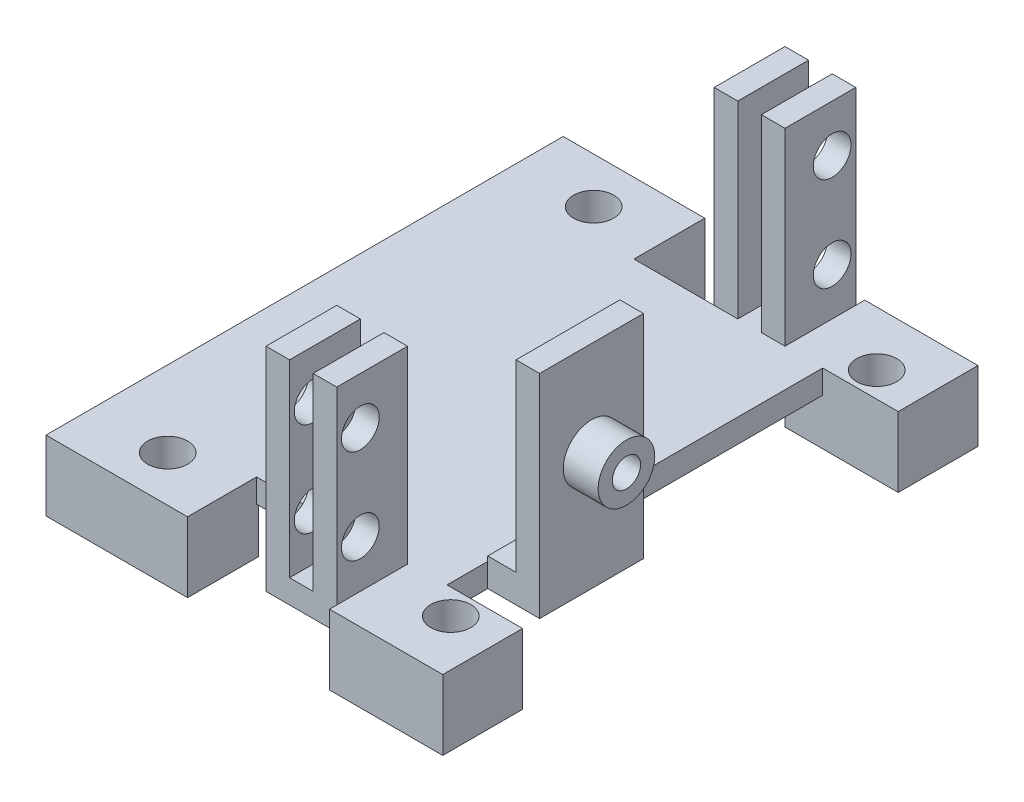
SolidWorks part; units mm, degrees
ref_plane "前视基准面" through (0, 0, 0) normal (0, 0, 1) x (1, 0, 0)
ref_plane "上视基准面" through (0, 0, 0) normal (0, 1, 0) x (1, 0, 0)
ref_plane "右视基准面" through (0, 0, 0) normal (1, 0, 0) x (0, 0, -1)
other "Configuration Table"
sketch "草图1" plane through (0, 0, 0) normal (0, 1, 0) x (1, 0, 0)
  line L1 (-105.8589, 60.8313) -> (105.8589, 60.8313)
  line L2 (-105.8589, 60.8313) -> (-105.8589, -60.8313)
  line L3 (-105.8589, -60.8313) -> (105.8589, -60.8313)
  line L4 (105.8589, 60.8313) -> (105.8589, -60.8313)
  line L5 (-105.8589, 60.8313) -> (105.8589, -60.8313) construction
  line L6 (-105.8589, -60.8313) -> (105.8589, 60.8313) construction
  point P0 (0, 0)
extrude "凸台-拉伸1" add sketch "草图1" along normal blind 10
sketch "草图2" plane through (0, 10, 0) normal (0, 1, 0) x (1, 0, 0)
  line L1 (-48.8589, 39.8117) -> (-43.8589, 39.8117)
  line L2 (-48.8589, 39.8117) -> (-48.8589, 54.8117)
  line L3 (-48.8589, 54.8117) -> (-43.8589, 54.8117)
  line L4 (-43.8589, 39.8117) -> (-43.8589, 54.8117)
  line L5 (-53.8589, 39.8117) -> (-58.8589, 39.8117)
  line L6 (-53.8589, 39.8117) -> (-53.8589, 54.8117)
  line L7 (-53.8589, 54.8117) -> (-58.8589, 54.8117)
  line L8 (-58.8589, 39.8117) -> (-58.8589, 54.8117)
  line L9 (-48.8589, -40.1883) -> (-43.8589, -40.1883)
  line L10 (-48.8589, -40.1883) -> (-48.8589, -55.1883)
  line L11 (-48.8589, -55.1883) -> (-43.8589, -55.1883)
  line L12 (-43.8589, -40.1883) -> (-43.8589, -55.1883)
  line L13 (-53.8589, -40.1883) -> (-58.8589, -40.1883)
  line L14 (-53.8589, -40.1883) -> (-53.8589, -55.1883)
  line L15 (-53.8589, -55.1883) -> (-58.8589, -55.1883)
  line L16 (-58.8589, -40.1883) -> (-58.8589, -55.1883)
  dimension "D1" = 5
  dimension "D2" = 5
  dimension "D3" = 15
  dimension "D4" = 15
  dimension "D5" = 5
  dimension "D6" = 5
  dimension "D7" = 15
  dimension "D8" = 15
extrude "凸台-拉伸2" add sketch "草图2" along normal up to surface (40 mm away)
sketch "草图3" plane through (0, 10, 0) normal (0, 1, 0) x (1, 0, 0)
  line L0 (-105.8589, 39.8117) -> (-58.8589, 39.8117)
  line L1 (-105.8589, 60.8313) -> (-105.8589, -60.8313) construction
  line L2 (-58.8589, 39.8117) -> (-58.8589, 54.8117)
  line L3 (-58.8589, 54.8117) -> (-43.8589, 54.8117)
  line L4 (-43.8589, 54.8117) -> (-43.8589, 39.8117)
  line L5 (-43.8589, 39.8117) -> (-35.8589, 39.8117)
  line L6 (-35.8589, 39.8117) -> (-35.8589, -40.1883)
  line L7 (-35.8589, -40.1883) -> (-43.8589, -40.1883)
  line L8 (-43.8589, -40.1883) -> (-43.8589, -55.1883)
  line L9 (-43.8589, -55.1883) -> (-48.8589, -55.1883)
  line L10 (-48.8589, -55.1883) -> (-48.8589, -40.1883)
  line L11 (-48.8589, -40.1883) -> (-53.8589, -40.1883)
  line L12 (-53.8589, -40.1883) -> (-53.8589, -55.1883)
  line L13 (-53.8589, -55.1883) -> (-58.8589, -55.1883)
  line L14 (-58.8589, -55.1883) -> (-58.8589, -40.1883)
  line L15 (-58.8589, -40.1883) -> (-106.7148, -40.1883)
  line L16 (-106.7148, -40.1883) -> (-105.8589, 39.8117)
extrude "切除-拉伸1" cut sketch "草图3" against normal through all both and the other way through all flip side to cut
sketch "草图4" plane through (0, 0, 0) normal (0, -1, 0) x (1, 0, 0)
  line L0 (-43.8589, 40.1883) -> (-35.8589, 40.1883) construction
  line L1 (-58.8589, 55.1883) -> (-43.8589, 55.1883)
  line L2 (-58.8589, 55.1883) -> (-58.8589, 40.1883)
  line L3 (-58.8589, 40.1883) -> (-43.8589, 40.1883)
  line L4 (-43.8589, 55.1883) -> (-43.8589, 40.1883)
  line L5 (-43.8589, 55.1883) -> (-43.8589, 40.1883) construction
extrude "凸台-拉伸3" add sketch "草图4" against normal blind 10
sketch "草图5" plane through (0, 0, 0) normal (0, -1, 0) x (1, 0, 0)
  line L1 (-225.4861, 144.4064) -> (25.5621, 144.4064)
  line L2 (-225.4861, 144.4064) -> (-225.4861, -64.4322)
  line L3 (-225.4861, -64.4322) -> (25.5621, -64.4322)
  line L4 (25.5621, 144.4064) -> (25.5621, -64.4322)
extrude "切除-拉伸2" cut sketch "草图5" against normal blind 5 and the other way through all
sketch "草图7" plane through (-43.8589, 0, 0) normal (1, 0, 0) x (0, 0, -1)
  circle A0 centre (-50.1883, 40) radius 4
  circle A1 centre (-50.1883, 20) radius 4
  circle A2 centre (49.8117, 40) radius 4
  circle A3 centre (49.8117, 20) radius 4
extrude "切除-拉伸3" cut sketch "草图7" against normal through all both and the other way through all
sketch "草图8" plane through (0, 5, 0) normal (0, -1, 0) x (1, 0, 0)
  line L0 (-126.1066, 20.1883) -> (-2.0025, 20.1883)
  line L1 (-17.4589, -19.8117) -> (-130.3567, -19.8117)
  line L2 (-17.4589, -25.8117) -> (-17.4589, -13.8117) construction
  line L4 (-43.8589, 40.1883) -> (-35.8589, 40.1883) construction
  line L6 (-29.8589, -19.8117) -> (-29.8589, 25.3599) construction
  line L7 (-35.8589, 40.1883) -> (-35.8589, -39.8117) construction
  line L9 (-35.8589, 31.1883) -> (-29.8589, 31.1883)
  line L10 (-35.8589, 31.1883) -> (-35.8589, 9.1883)
  line L11 (-35.8589, 9.1883) -> (-29.8589, 9.1883)
  line L12 (-29.8589, 31.1883) -> (-29.8589, 9.1883)
  dimension "D1" = 20
  dimension "D2" = 11
  dimension "D3" = 11
  dimension "D4" = 0
extrude "凸台-拉伸6" add sketch "草图8" against normal up to surface (6 mm away) contours L10 L9 L12 L11
sketch "草图9" plane through (0, 5, 0) normal (0, -1, 0) x (1, 0, 0)
  line L0 (-34.8589, 39.1883) -> (-34.8589, 31.1883)
  line L1 (-34.8589, 31.1883) -> (-29.2078, 25.5372)
  line L2 (-29.2078, 25.5372) -> (-29.2078, 39.1883)
  line L3 (-29.2078, 39.1883) -> (-34.8589, 39.1883)
extrude "切除-拉伸4" cut sketch "草图9" against normal through all both and the other way through all
sketch "草图10" plane through (-29.8589, 0, 0) normal (1, 0, 0) x (0, 0, -1)
  line L0 (19.8117, 30) -> (54.8117, 30)
  line L1 (-9.1883, 5) -> (-31.1883, 5)
  line L2 (-9.1883, 5) -> (-9.1883, 50)
  line L3 (-9.1883, 50) -> (-31.1883, 50)
  line L4 (-31.1883, 5) -> (-31.1883, 50)
  line L5 (54.8117, 50) -> (54.8117, 5) construction
  line L6 (-55.1883, 30) -> (-20.1883, 30) construction
  line L7 (-55.1883, 50) -> (-55.1883, 5) construction
  line L8 (-20.1883, 57.2172) -> (-20.1883, -20.7993) construction
  line L9 (-9.1883, 5) -> (39.8117, 5) construction
  line M8 (-9.1883, 11) -> (-26.1883, 11)
  line M9 (-26.1883, 11) -> (-26.1883, 5)
  line M10 (-26.1883, 5) -> (-9.1883, 5)
  line M11 (-9.1883, 5) -> (-9.1883, 11)
  dimension "D2" = 11
  dimension "D1" = 35
  dimension "D3" = 45
extrude "凸台-拉伸7" add sketch "草图10" along normal blind 5 contours L4 L1 L2 L3 M9 M8 | M11 M8 M9 M10
sketch "草图11" plane through (-24.8589, 0, 0) normal (1, 0, 0) x (0, 0, -1)
  line L0 (-20.1883, 50) -> (-20.1883, 5) construction
  line L1 (-9.1883, 50) -> (-31.1883, 50) construction
  line L2 (-9.1883, 5) -> (-31.1883, 5) construction
  line L3 (-9.1883, 27.5) -> (-31.1883, 27.5) construction
  line L4 (-9.1883, 5) -> (-9.1883, 50) construction
  line L5 (-31.1883, 5) -> (-31.1883, 50) construction
  circle A0 centre (-20.1883, 27.5) radius 11
  dimension "D1" = 22
extrude "凸台-拉伸8" add sketch "草图11" against normal up to surface (0.6 mm away)
sketch "草图12" plane through (-24.8589, 0, 0) normal (1, 0, 0) x (0, 0, -1)
  line L0 (-20.1883, 50) -> (-20.1883, 5) construction
  line L1 (-9.1883, 50) -> (-31.1883, 50) construction
  line L2 (-9.1883, 5) -> (-31.1883, 5) construction
  line L3 (-9.1883, 27.5) -> (-31.1883, 27.5) construction
  line L4 (-9.1883, 5) -> (-9.1883, 50) construction
  line L5 (-31.1883, 5) -> (-31.1883, 50) construction
  circle A0 centre (-20.1883, 27.5) radius 6
  dimension "D1" = 12
extrude "凸台-拉伸9" add sketch "草图12" along normal up to surface (7.4 mm away) contours A0
sketch "草图13" plane through (-17.4589, 0, 0) normal (1, 0, 0) x (0, 0, -1)
  circle A0 centre (-20.1883, 27.5) radius 3
  dimension "D1" = 6
extrude "切除-拉伸10" cut sketch "草图13" against normal blind 3 and the other way through all
sketch "草图14" plane through (0, 5, 0) normal (0, -1, 0) x (-1, 0, 0)
  line L0 (34.8589, -31.1883) -> (29.8589, -31.1883)
  line L1 (29.8589, -31.1883) -> (29.8589, -26.1883)
  line L2 (29.8589, -26.1883) -> (34.8589, -31.1883)
extrude "凸台-拉伸10" add sketch "草图14" against normal up to surface (45 mm away) up to face at (-27.3589, 50, 20.1883)
sketch "草图15" plane through (-24.8589, 0, 0) normal (1, 0, 0) x (0, 0, -1)
  circle A0 centre (-20.1883, 27.5) radius 9.3191
extrude "切除-拉伸11" cut sketch "草图15" along normal blind 38
sketch "草图16" plane through (-24.8589, 0, 0) normal (1, 0, 0) x (0, 0, -1)
  line L0 (19.8117, 30) -> (-62.797, 30) construction
  line L1 (-20.1883, 50) -> (-20.1883, 5) construction
  line L2 (-9.1883, 50) -> (-31.1883, 50) construction
  line L3 (-9.1883, 5) -> (-31.1883, 5) construction
  circle A0 centre (-20.1883, 30) radius 6
  dimension "D1" = 12
extrude "凸台-拉伸11" add sketch "草图16" along normal up to surface (7.4 mm away)
sketch "草图17" plane through (-17.4589, 0, 0) normal (1, 0, 0) x (0, 0, -1)
  circle A0 centre (-20.1883, 30) radius 3
  dimension "D1" = 6
extrude "切除-拉伸12" cut sketch "草图17" against normal blind 5
ref_plane "基准面1" through (0, 0, 0.1883) normal (0, 0, -1) x (-1, 0, 0)
sketch "草图18" plane through (0, 10, 0) normal (0, 1, 0) x (1, 0, 0)
  line L0 (-105.8589, 39.8117) -> (-105.8589, -40.1883) construction
  line L5 (-105.8589, 39.8117) -> (-75.8589, 39.8117)
  line L6 (-105.8589, 39.8117) -> (-105.8589, 54.8117)
  line L7 (-105.8589, 54.8117) -> (-75.8589, 54.8117)
  line L8 (-75.8589, 39.8117) -> (-75.8589, 54.8117)
  line L9 (-58.8589, 39.8117) -> (-105.8589, 39.8117) construction
  dimension "D1" = 30
  dimension "D2" = 15
extrude "凸台-拉伸12" add sketch "草图18" against normal up to surface (14.8505 mm away)
sketch "草图19" plane through (0, 10, 0) normal (0, 1, 0) x (1, 0, 0)
  circle A0 centre (-89.7427, 45.1412) radius 4.25
sketch "草图20" plane through (0, 10, 0) normal (0, 1, 0) x (1, 0, 0)
  line L1 (-105.8589, -40.1883) -> (-74.7427, -56.8347)
  line L2 (-105.8589, -40.1883) -> (-105.8589, -57.0972)
  line L3 (-105.8589, -57.0972) -> (-74.7427, -57.0972)
  line L4 (-74.7427, -56.8347) -> (-74.7427, -57.0972)
  circle A0 centre (-89.7427, -45.5178) radius 5.025 construction
  dimension "D1" = 15
extrude "凸台-拉伸13" add sketch "草图20" against normal up to surface (14.8505 mm away)
sketch "草图21" plane through (0, 10, 0) normal (0, 1, 0) x (1, 0, 0)
  circle A0 centre (-89.7427, -45.5178) radius 4.25
sketch "草图22" plane through (0, 10, 0) normal (0, 1, 0) x (1, 0, 0)
  line L6 (-43.8589, 39.8117) -> (-19.8589, 39.8117)
  line L7 (-43.8589, 39.8117) -> (-43.8589, 56.7207)
  line L8 (-43.8589, 56.7207) -> (-19.8589, 56.7207)
  line L9 (-19.8589, 39.8117) -> (-19.8589, 56.7207)
  dimension "D1" = 16.909
  dimension "D2" = 24
extrude "凸台-拉伸14" add sketch "草图22" against normal up to surface (14.8505 mm away)
sketch "草图23" plane through (0, 10, 0) normal (0, 1, 0) x (1, 0, 0)
  circle A0 centre (-29.7427, 45.1412) radius 4.25
extrude "切除-拉伸15" cut sketch "草图23" against normal blind 60
sketch "草图24" plane through (0, -4.8505, 0) normal (0, 1, 0) x (1, 0, 0)
  line L0 (-43.8589, -40.1883) -> (-43.8589, -57.0972)
  line L2 (-43.8589, -57.0972) -> (-19.7427, -40.2333)
  line L3 (-19.7427, -40.2333) -> (-19.7427, -40.1883)
  line L4 (-19.7427, -40.1883) -> (-43.8589, -40.1883)
  circle A0 centre (-29.7427, -45.5178) radius 5.025 construction
  dimension "D1" = 10
extrude "凸台-拉伸15" add sketch "草图24" along normal up to surface (14.8505 mm away) up to face at (-29.7427, 10, -40.8912)
sketch "草图25" plane through (0, 10, 0) normal (0, 1, 0) x (1, 0, 0)
  circle A0 centre (-29.7427, -45.5178) radius 4.25
extrude "切除-拉伸16" cut sketch "草图25" against normal blind 60
extrude "切除-拉伸17" cut sketch "草图19" against normal blind 60 contours A0
sketch "草图26" plane through (0, 10, 0) normal (0, 1, 0) x (1, 0, 0)
  line L1 (-105.8589, -40.1883) -> (-67.8142, -40.1883)
  line L2 (-105.8589, -40.1883) -> (-105.8589, -61.5344)
  line L3 (-105.8589, -61.5344) -> (-67.8142, -61.5344)
  line L4 (-67.8142, -40.1883) -> (-67.8142, -61.5344)
  line L5 (-43.8589, -57.0972) -> (-19.1591, -57.0972)
  line L6 (-43.8589, -57.0972) -> (-43.8589, -40.1883)
  line L7 (-43.8589, -40.1883) -> (-19.1591, -40.1883)
  line L8 (-19.1591, -57.0972) -> (-19.1591, -40.1883)
extrude "切除-拉伸18" cut sketch "草图26" against normal blind 60
mirror "镜向1" about plane through (0, 0, 0) normal (0, 0, 1) of "切除-拉伸17", "切除-拉伸15", "凸台-拉伸14", "凸台-拉伸12"
sketch "草图27" plane through (0, 50, 0) normal (0, 1, 0) x (1, 0, 0)
  line L0 (-29.8589, -26.1883) -> (-29.8589, -9.1883) construction
  line L1 (-29.8589, -18.2814) -> (-36.1801, -18.2814)
  line L2 (-29.8589, -18.2814) -> (-29.8589, -33.0286)
  line L3 (-29.8589, -33.0286) -> (-36.1801, -33.0286)
  line L4 (-36.1801, -18.2814) -> (-36.1801, -33.0286)
extrude "切除-拉伸19" cut sketch "草图27" against normal up to surface (39 mm away) up to face at (-33.2589, 11, 21.3883)
